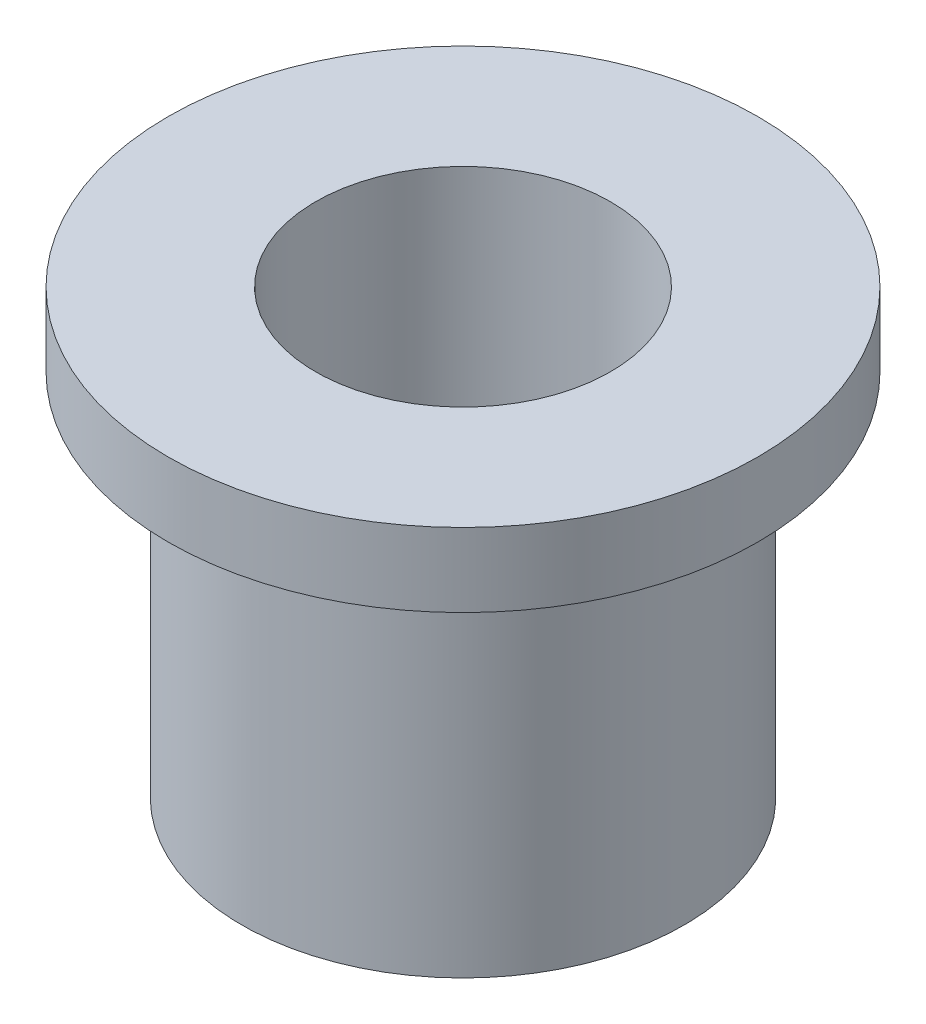
SolidWorks part; units mm, degrees
ref_plane "Front Plane" through (0, 0, 0) normal (0, 0, 1) x (1, 0, 0)
ref_plane "Top Plane" through (0, 0, 0) normal (0, 1, 0) x (1, 0, 0)
ref_plane "Right Plane" through (0, 0, 0) normal (1, 0, 0) x (0, 0, -1)
sketch "Sketch1" plane through (0, 0, 0) normal (0, 1, 0) x (1, 0, 0)
  circle A0 centre (0, 0) radius 3.175
  circle A1 centre (0, 0) radius 4.7625
  point P4 (0, 0)
extrude "Boss-Extrude1" add sketch "Sketch1" along normal blind 9.525
sketch "Sketch2" plane through (0, 9.525, 0) normal (0, 1, 0) x (1, 0, 0)
  circle A0 centre (0, 0) radius 3.175
  circle A1 centre (0, 0) radius 6.35
extrude "Boss-Extrude2" add sketch "Sketch2" against normal blind 1.5875
